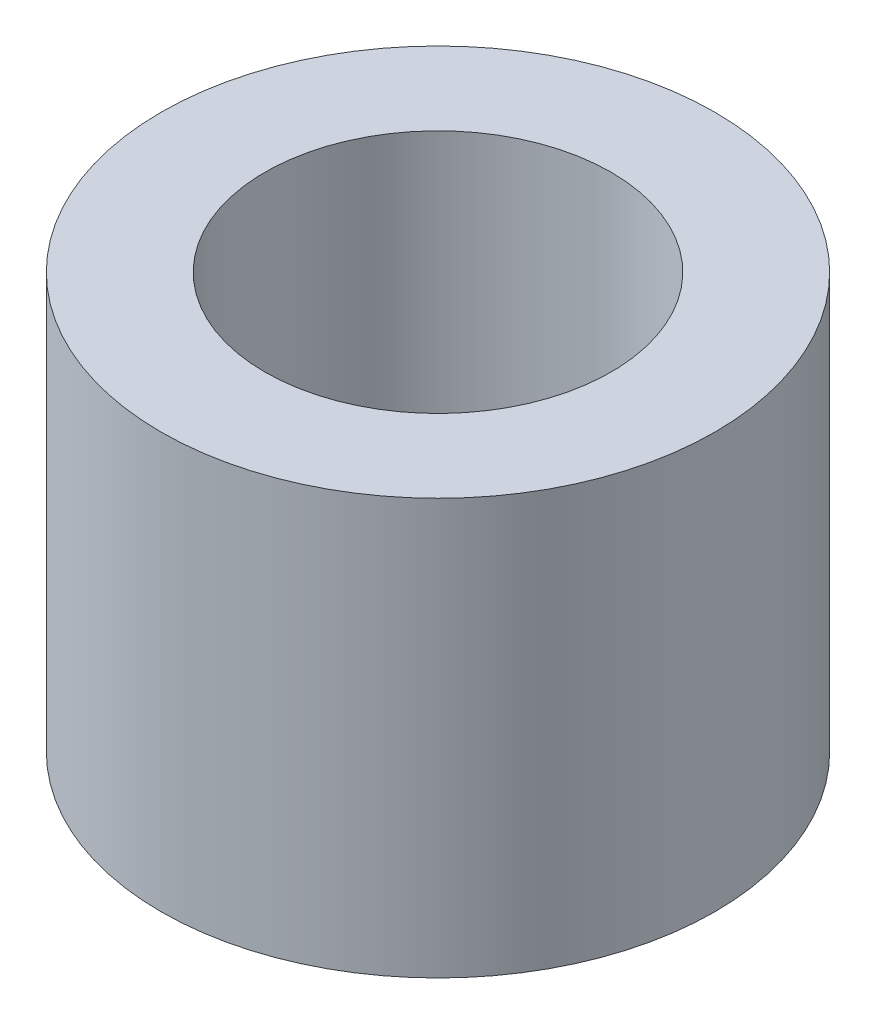
SolidWorks part; units mm, degrees
material "黄铜"
ref_plane "前视基准面" through (0, 0, 0) normal (0, 0, 1) x (1, 0, 0)
ref_plane "上视基准面" through (0, 0, 0) normal (0, 1, 0) x (1, 0, 0)
ref_plane "右视基准面" through (0, 0, 0) normal (1, 0, 0) x (0, 0, -1)
other "Configuration Table"
sketch "草图1" plane through (0, 0, 0) normal (0, 1, 0) x (1, 0, 0)
  circle A0 centre (0, 0) radius 4
  circle A1 centre (0, 0) radius 2.5
  dimension "D1" = 8
  dimension "D2" = 5
extrude "凸台-拉伸1" add sketch "草图1" along normal mid plane 6
